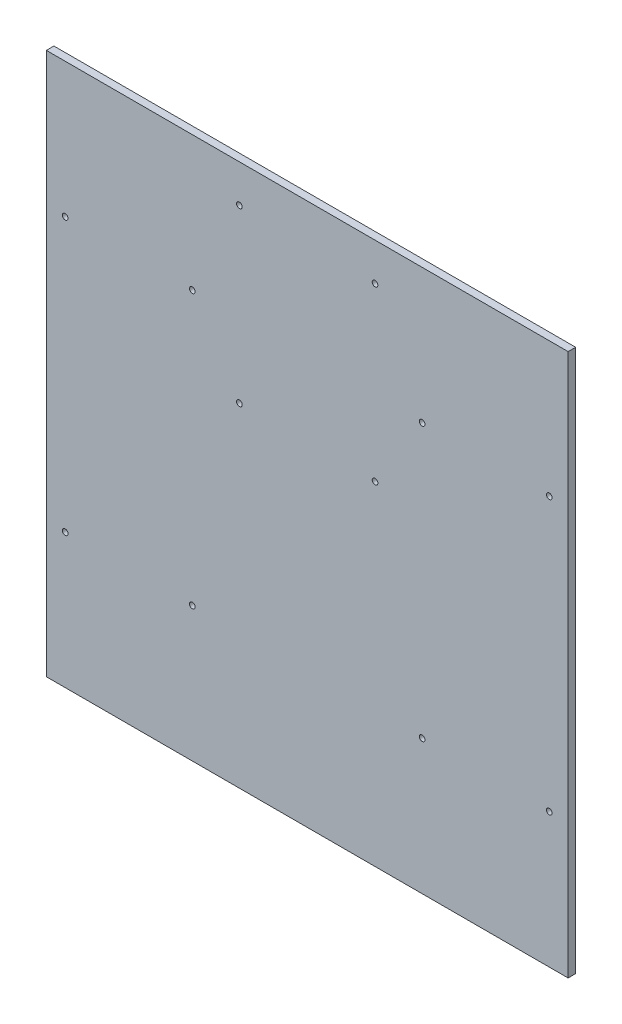
SolidWorks part; units mm, degrees
ref_plane "Plan de face" through (0, 0, 0) normal (0, 0, 1) x (1, 0, 0)
ref_plane "Plan de dessus" through (0, 0, 0) normal (0, 1, 0) x (1, 0, 0)
ref_plane "Plan de droite" through (0, 0, 0) normal (1, 0, 0) x (0, 0, -1)
sketch "Esquisse1" plane through (0, 0, 0) normal (0, 0, 1) x (1, 0, 0)
  line L0 (182.4092, -30.3196) -> (182.4092, -175.3196) construction
  line L1 (-17.0908, 41.1804) -> (259.9092, 41.1804)
  line L2 (-17.0908, 41.1804) -> (-17.0908, -246.8196)
  line L3 (-17.0908, -246.8196) -> (259.9092, -246.8196)
  line L4 (259.9092, 41.1804) -> (259.9092, -246.8196)
  line L5 (249.9092, -30.3196) -> (249.9092, -175.3196) construction
  line L6 (121.4092, -161.0098) -> (121.4092, -45.855) construction
  line L7 (-7.0908, -30.3196) -> (-7.0908, -175.3196) construction
  line L8 (60.4092, -30.3196) -> (60.4092, -175.3196) construction
  circle A0 centre (182.4092, -175.3196) radius 1.5
  circle A1 centre (182.4092, -30.3196) radius 1.5
  circle A2 centre (249.9092, -30.3196) radius 1.5
  circle A3 centre (249.9092, -175.3196) radius 1.5
  circle A4 centre (-7.0908, -175.3196) radius 1.5
  circle A5 centre (-7.0908, -30.3196) radius 1.5
  circle A6 centre (60.4092, -30.3196) radius 1.5
  circle A7 centre (60.4092, -175.3196) radius 1.5
  dimension "D6" = 77.5
  dimension "D9" = 138.5
  dimension "D1" = 277
  dimension "D2" = 288
  dimension "D3" = 10
  dimension "D4" = 71.5
  dimension "D5" = 71.5
  dimension "D7" = 71.5
  dimension "D8" = 71.5
extrude "Extrusion1" add sketch "Esquisse1" along normal blind 4
sketch "Esquisse2" plane through (0, 0, 4) normal (0, 0, 1) x (1, 0, 0)
  line L0 (121.4092, 41.1804) -> (121.4092, -246.8196) construction
  line L3 (259.9092, 41.1804) -> (-17.0908, 41.1804) construction
  line L5 (157.4092, 21.1804) -> (157.4092, -69.8196) construction
  line L12 (-17.0908, -246.8196) -> (259.9092, -246.8196) construction
  line L13 (85.4092, 21.1804) -> (85.4092, -69.8196) construction
  circle A0 centre (85.4092, 21.1804) radius 1.5
  circle A1 centre (85.4092, -69.8196) radius 1.5
  circle A6 centre (157.4092, -69.8196) radius 1.5
  circle A7 centre (157.4092, 21.1804) radius 1.5
  dimension "D1" = 36
  dimension "D5" = 91
  dimension "D6" = 20
extrude "Extrusion2" cut sketch "Esquisse2" against normal blind 10
